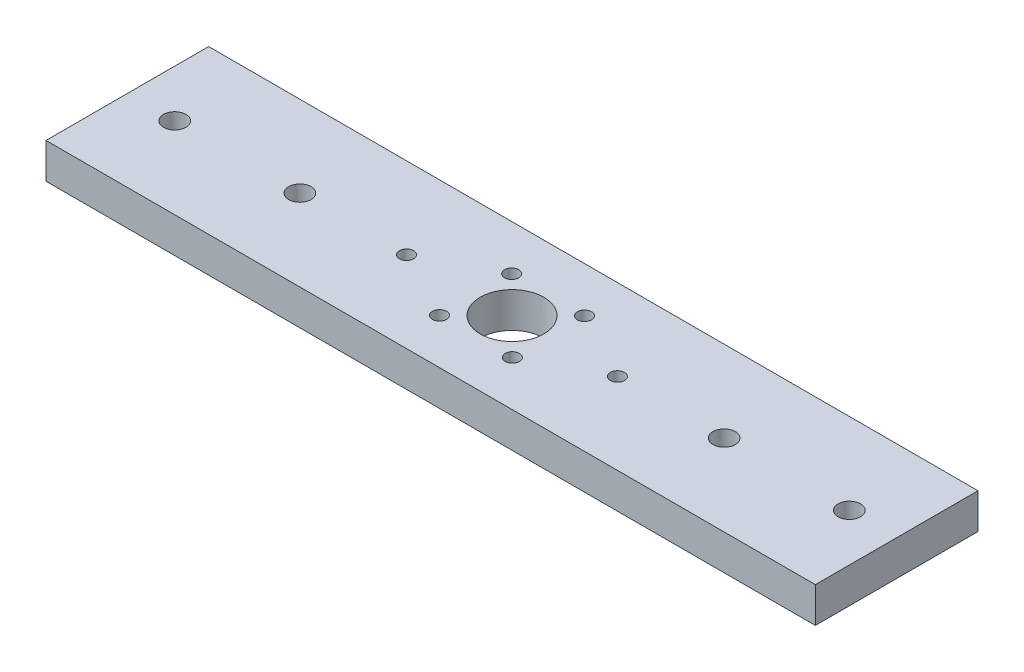
SolidWorks part; units mm, degrees
ref_plane "Front Plane" through (0, 0, 0) normal (0, 0, 1) x (1, 0, 0)
ref_plane "Top Plane" through (0, 0, 0) normal (0, 1, 0) x (1, 0, 0)
ref_plane "Right Plane" through (0, 0, 0) normal (1, 0, 0) x (0, 0, -1)
sketch "Sketch1" plane through (0, 0, 0) normal (0, 1, 0) x (1, 0, 0)
  line L1 (0, 0) -> (108.8, 0)
  line L2 (0, 0) -> (0, 23)
  line L3 (0, 23) -> (108.8, 23)
  line L4 (108.8, 0) -> (108.8, 23)
  dimension "D1" = 108.8
  dimension "D2" = 23
extrude "Mount Base" add sketch "Sketch1" along normal blind 5
sketch "Sketch2" plane through (0, 5, 0) normal (0, 1, 0) x (1, 0, 0)
  line L0 (108.8, 0) -> (108.8, 23) construction
  line L1 (0, 0) -> (108.8, 0) construction
  circle A0 centre (59.55, 16.6) radius 1
  circle A1 centre (59.55, 6.4) radius 1
  circle A2 centre (49.25, 6.4) radius 1
  circle A3 centre (49.25, 16.6) radius 1
  circle A4 centre (69.31, 11.5) radius 1
  circle A5 centre (39.49, 11.5) radius 1
  circle A6 centre (54.4, 11.5) radius 4.5
  point P16 (108.8, 11.5)
  point P19 (54.4, 0)
  dimension "D4" = 9
  dimension "D1" = 2
  dimension "D3" = 10.3
  dimension "D5" = 5.15
  dimension "D6" = 5.1
  dimension "D2" = 10.2
  dimension "D7" = 14.91
  dimension "D8" = 14.91
extrude "Bracket Screw Holes" cut sketch "Sketch2" against normal up to surface (5 mm away) up to face at (54.4, 0, -11.5)
sketch "Sketch3" plane through (0, 5, 0) normal (0, 1, 0) x (1, 0, 0)
  line L0 (0, 23) -> (0, 0) construction
  circle A0 centre (6.7, 11.5) radius 1.5875
  circle A1 centre (24.4, 11.5) radius 1.5875
  circle A2 centre (84.4, 11.5) radius 1.5875
  circle A3 centre (102.1, 11.5) radius 1.5875
  circle A4 centre (54.4, 11.5) radius 4.5 construction
  point P8 (0, 0)
  point P13 (0, 11.5)
  dimension "D1" = 3.175
  dimension "D2" = 17.7
  dimension "D3" = 17.7
  dimension "D4" = 30
  dimension "D5" = 30
extrude "Antenna Screw Holes" cut sketch "Sketch3" against normal up to surface (5 mm away) up to face at (59.55, 0, -7.4)
equation "\"D8@Sketch2\"=\"D7@Sketch2\""
equation "\"D7@Sketch2\"=8.76+\"D3@Sketch2\"/2 + \"D1@Sketch2\"/2"
equation "\"D6@Sketch2\"=\"D2@Sketch2\"/2"
equation "\"D5@Sketch2\"=\"D3@Sketch2\"/2"
equation "\"D3@Sketch3\"=\"D2@Sketch3\""
equation "\"D5@Sketch3\"=\"D4@Sketch3\""
